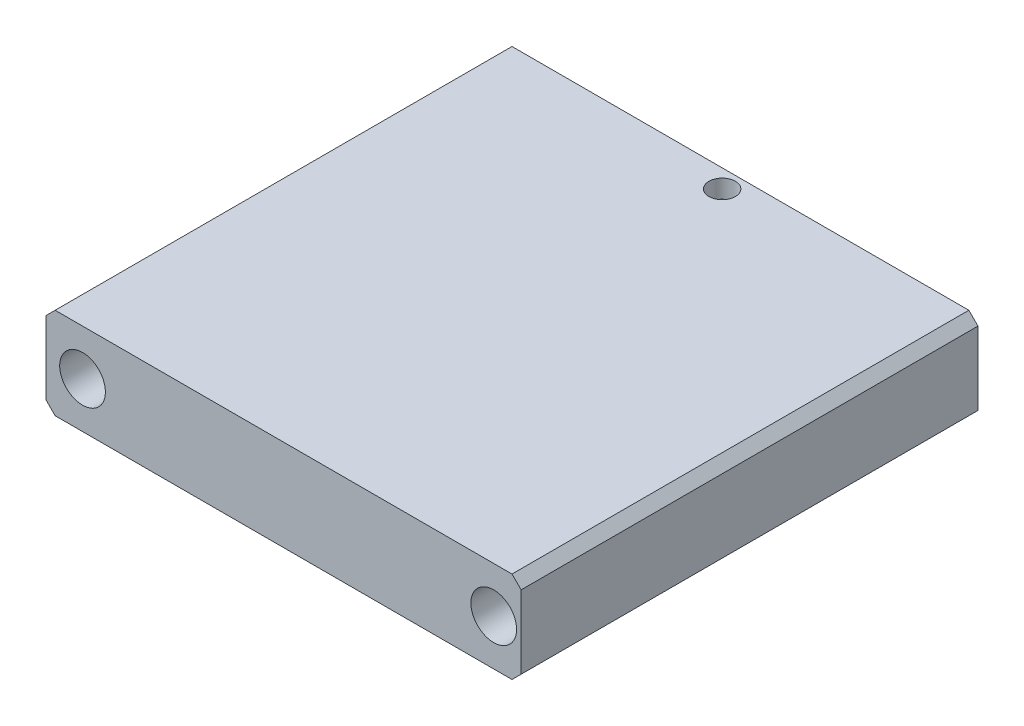
SolidWorks part; units mm, degrees
ref_plane "Front Plane" through (0, 0, 0) normal (0, 0, 1) x (1, 0, 0)
ref_plane "Top Plane" through (0, 0, 0) normal (0, 1, 0) x (1, 0, 0)
ref_plane "Right Plane" through (0, 0, 0) normal (1, 0, 0) x (0, 0, -1)
sketch "Sketch1" plane through (0, 0, 0) normal (0, 0, 1) x (1, 0, 0)
  line L0 (42.8724, -9.5044) -> (43.8724, -8.5044)
  line L1 (43.8724, -8.5044) -> (43.8724, -0.5044)
  line L2 (43.8724, -0.5044) -> (42.8724, 0.4956)
  line L3 (42.8724, 0.4956) -> (-7.1276, 0.4956)
  line L4 (-7.1276, 0.4956) -> (-8.1276, -0.5044)
  line L5 (-8.1276, -0.5044) -> (-8.1276, -8.5044)
  line L6 (-8.1276, -8.5044) -> (-7.1276, -9.5044)
  line L7 (-7.1276, -9.5044) -> (42.8724, -9.5044)
  circle A0 centre (39.8724, -4.5044) radius 2.5
  circle A1 centre (-4.1276, -4.5044) radius 2.5
  point P12 (43.3582, 10.9044)
  point P13 (0, 0)
  dimension "D1" = 5
  dimension "D2" = 5
  dimension "D3" = 10
  dimension "D4" = 52
  dimension "D5" = 4
  dimension "D6" = 44
  dimension "D7" = 5
  dimension "D8" = 1
extrude "Boss-Extrude1" add sketch "Sketch1" along normal blind 50 contours L7 L0 L1 L2 L3 L4 L5 L6
sketch "Sketch2" plane through (0, 0, 50) normal (0, 0, 1) x (1, 0, 0)
  line L0 (42.8724, 0.4956) -> (-7.1276, 0.4956) construction
  line L1 (-8.1276, -0.5044) -> (-8.1276, -8.5044) construction
  circle A0 centre (-4.1276, -4.5044) radius 2.5
  circle A1 centre (40.8724, -4.5044) radius 2.5
  point P4 (0, 0)
  point P7 (0, 0)
  point P10 (0, 0)
  point P13 (0, 0)
  dimension "D1" = 5
  dimension "D2" = 5
  dimension "D3" = 45
  dimension "D4" = 5
  dimension "D5" = 4
extrude "Cut-Extrude1" cut sketch "Sketch2" against normal through all contours A0 | A1
sketch "Sketch3" plane through (0, -9.5044, 0) normal (0, -1, 0) x (1, 0, 0)
  line L0 (-7.1276, 0) -> (42.8724, 0) construction
  line L1 (-8.1276, 50) -> (-8.1276, 0) construction
  circle A0 centre (17.8724, 2) radius 1.45
  dimension "D1" = 2.9
  dimension "D2" = 2
  dimension "D3" = 26
extrude "Cut-Extrude2" cut sketch "Sketch3" against normal through all
sketch "Sketch4" plane through (0, 0, 0) normal (0, 0, -1) x (-1, 0, 0)
  line L0 (-42.8724, 0.4956) -> (7.1276, 0.4956) construction
  line L1 (-20.8724, -1.5044) -> (-14.8724, -1.5044)
  line L2 (-20.8724, -1.5044) -> (-20.8724, -7.5044)
  line L3 (-20.8724, -7.5044) -> (-14.8724, -7.5044)
  line L4 (-14.8724, -1.5044) -> (-14.8724, -7.5044)
  line L5 (-20.8724, -1.5044) -> (-14.8724, -7.5044) construction
  line L6 (-20.8724, -7.5044) -> (-14.8724, -1.5044) construction
  line L8 (8.1276, -0.5044) -> (8.1276, -8.5044) construction
  point P0 (-17.8724, -4.5044)
  point P9 (-24.0794, -11.0638)
  point P10 (0, 0)
  dimension "D1" = 6
  dimension "D2" = 6
  dimension "D3" = 26
  dimension "D4" = 5
extrude "Cut-Extrude4" cut sketch "Sketch4" against normal blind 6 contours L4 L3 L2 L1
